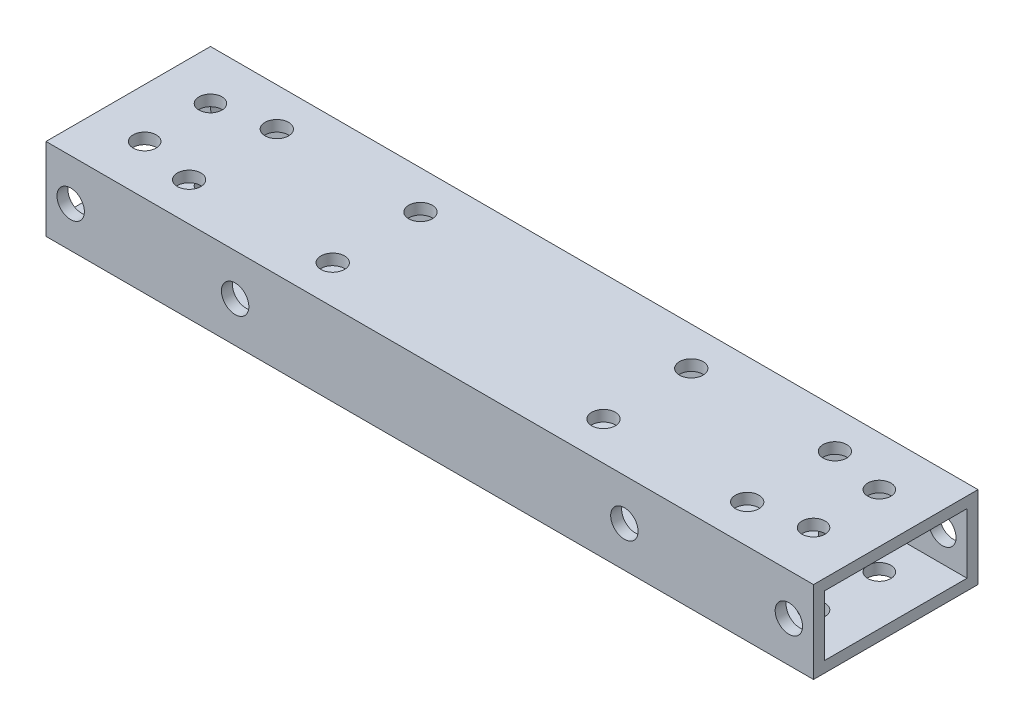
SolidWorks part; units mm, degrees
material "1060 合金"
ref_plane "前视基准面" through (0, 0, 0) normal (0, 0, 1) x (1, 0, 0)
ref_plane "上视基准面" through (0, 0, 0) normal (0, 1, 0) x (1, 0, 0)
ref_plane "右视基准面" through (0, 0, 0) normal (1, 0, 0) x (0, 0, -1)
sketch "草图1" plane through (0, 0, 0) normal (1, 0, 0) x (0, 0, -1)
  line L1 (0, 0) -> (30, 0)
  line L2 (0, 0) -> (0, 15)
  line L3 (0, 15) -> (30, 15)
  line L4 (30, 0) -> (30, 15)
  line L5 (2, 13) -> (28, 13)
  line L6 (2, 13) -> (2, 2)
  line L7 (2, 2) -> (28, 2)
  line L8 (28, 13) -> (28, 2)
  dimension "D1" = 15
  dimension "D2" = 30
  dimension "D3" = 2
  dimension "D4" = 2
  dimension "D5" = 2
  dimension "D6" = 2
extrude "凸台-拉伸1" add sketch "草图1" along normal blind 140
sketch "草图2" plane through (0, 0, 0) normal (0, -1, 0) x (1, 0, 0)
  circle A0 centre (19.1, -7) radius 2.15
  circle A1 centre (19.1, -23) radius 2.15
  circle A2 centre (45.3, -23) radius 2.15
  circle A3 centre (45.3, -7) radius 2.15
extrude "切除-拉伸1" cut sketch "草图2" against normal through all
sketch "草图3" plane through (0, 0, 0) normal (0, -1, 0) x (1, 0, 0)
  circle A0 centre (94.7, -7) radius 2.15
  circle A1 centre (120.9, -7) radius 2.15
  circle A2 centre (120.9, -23) radius 2.15
  circle A3 centre (94.7, -23) radius 2.15
extrude "切除-拉伸2" cut sketch "草图3" against normal through all both and the other way through all
sketch "草图4" plane through (0, 0, 0) normal (0, -1, 0) x (1, 0, 0)
  circle A0 centre (131, -9) radius 2.1
  circle A1 centre (131, -21) radius 2.1
extrude "切除-拉伸3" cut sketch "草图4" against normal through all
sketch "草图5" plane through (0, 0, 0) normal (0, -1, 0) x (1, 0, 0)
  circle A0 centre (9, -9) radius 2.1
  circle A1 centre (9, -21) radius 2.1
extrude "切除-拉伸4" cut sketch "草图5" against normal through all
sketch "草图6" plane through (0, 0, 0) normal (0, 0, 1) x (1, 0, 0)
  circle A0 centre (4.5, 7.4) radius 2.5
  circle A1 centre (34.5, 7.4) radius 2.5
  circle A2 centre (105.5, 7.4) radius 2.5
  circle A3 centre (135.5, 7.4) radius 2.5
extrude "切除-拉伸5" cut sketch "草图6" against normal through all
